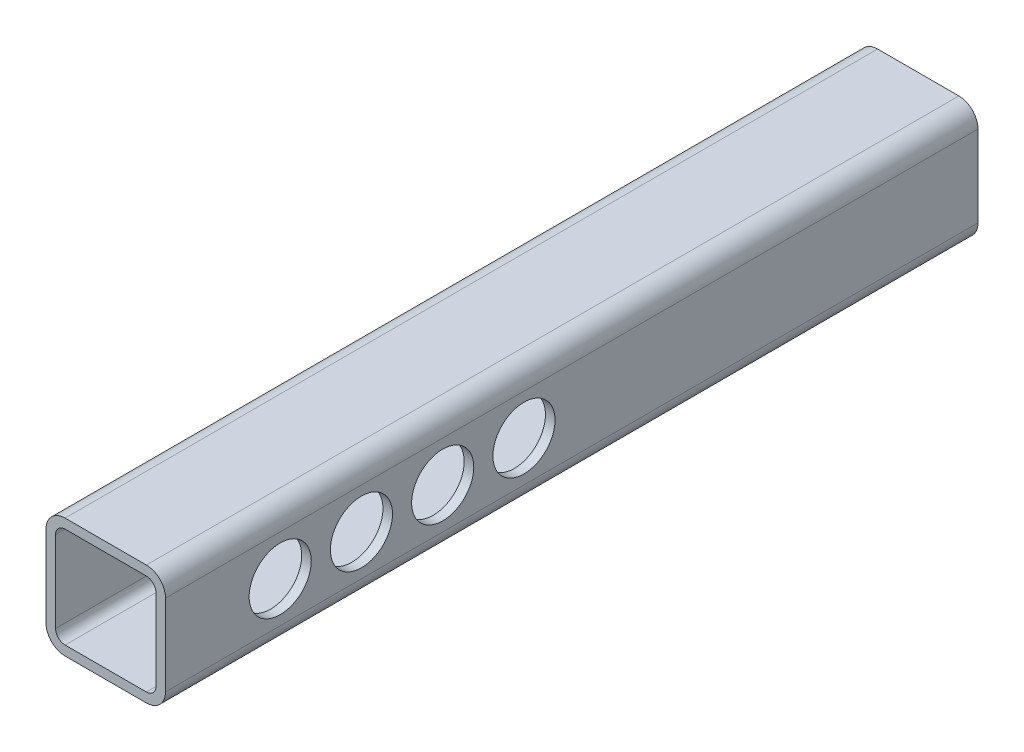
SolidWorks part; units mm, degrees
material "1060 Сплав"
ref_plane "Front" through (0, 0, 0) normal (0, 0, 1) x (1, 0, 0)
ref_plane "Top" through (0, 0, 0) normal (0, 1, 0) x (1, 0, 0)
ref_plane "Right" through (0, 0, 0) normal (1, 0, 0) x (0, 0, -1)
sketch "Эскиз1" plane through (0, 0, 0) normal (0, 0, 1) x (1, 0, 0)
  line L0 (-10.5, -8.5) -> (-10.5, 8.5)
  line L1 (8.5, -12.5) -> (-8.5, -12.5)
  line L2 (12.5, -8.5) -> (12.5, 8.5)
  line L3 (8.5, 12.5) -> (-8.5, 12.5)
  line L4 (-12.5, -8.5) -> (-12.5, 8.5)
  line L5 (12.5, -12.5) -> (-12.5, 12.5) construction
  line L6 (12.5, 12.5) -> (-12.5, -12.5) construction
  line L7 (8.5, 10.5) -> (-8.5, 10.5)
  line L8 (10.5, -8.5) -> (10.5, 8.5)
  line L9 (8.5, -10.5) -> (-8.5, -10.5)
  arc A0 (-12.5, -8.5) -> (-8.5, -12.5) centre (-8.5, -8.5) ccw
  arc A1 (8.5, -12.5) -> (12.5, -8.5) centre (8.5, -8.5) ccw
  arc A2 (12.5, 8.5) -> (8.5, 12.5) centre (8.5, 8.5) ccw
  arc A3 (-12.5, 8.5) -> (-8.5, 12.5) centre (-8.5, 8.5) cw
  arc A4 (-10.5, 8.5) -> (-8.5, 10.5) centre (-8.5, 8.5) cw
  arc A5 (10.5, 8.5) -> (8.5, 10.5) centre (8.5, 8.5) ccw
  arc A6 (8.5, -10.5) -> (10.5, -8.5) centre (8.5, -8.5) ccw
  arc A7 (-10.5, -8.5) -> (-8.5, -10.5) centre (-8.5, -8.5) ccw
  point P0 (0, 0)
  dimension "D3" = 4
  dimension "D1" = 25
  dimension "D2" = 25
  dimension "D4" = 2
extrude "Бобышка-Вытянуть1" add sketch "Эскиз1" along normal blind 170
sketch "Эскиз2" plane through (12.5, 0, 0) normal (1, 0, 0) x (0, 0, -1)
  line L1 (-170, -8.5) -> (-170, 8.5) construction
  circle A0 centre (-146, 0) radius 6.5
  circle A1 centre (-129, 0) radius 6.5
  circle A2 centre (-112, 0) radius 6.5
  circle A3 centre (-95, 0) radius 6.5
  dimension "D1" = 13
  dimension "D2" = 24
  dimension "D3" = 17
  dimension "D4" = 17
  dimension "D5" = 17
extrude "Вырез-Вытянуть1" cut sketch "Эскиз2" against normal through all
